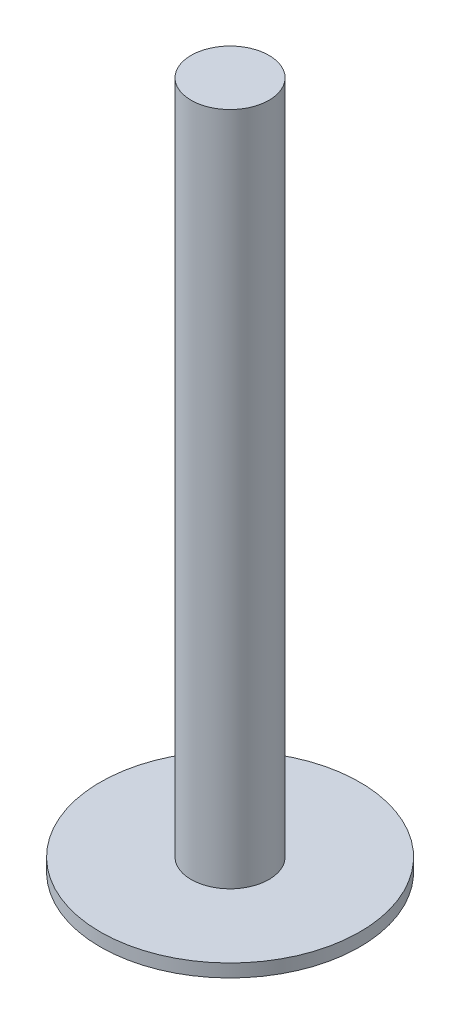
SolidWorks part; units mm, degrees
material "5052-H34"
ref_plane "正面" through (0, 0, 0) normal (0, 0, 1) x (1, 0, 0)
ref_plane "平面" through (0, 0, 0) normal (0, 1, 0) x (1, 0, 0)
ref_plane "右側面" through (0, 0, 0) normal (1, 0, 0) x (0, 0, -1)
sketch "ｽｹｯﾁ1" plane through (0, 0, 0) normal (0, 1, 0) x (1, 0, 0)
  circle A0 centre (0, 0) radius 5
  dimension "D1" = 10
extrude "ﾎﾞｽ - 押し出し1" add sketch "ｽｹｯﾁ1" along normal blind 0.5
sketch "ｽｹｯﾁ2" plane through (0, 0.5, 0) normal (0, 1, 0) x (1, 0, 0)
  circle A0 centre (0, 0) radius 1.5
  dimension "D1" = 3
extrude "ﾎﾞｽ - 押し出し2" add sketch "ｽｹｯﾁ2" along normal blind 26
